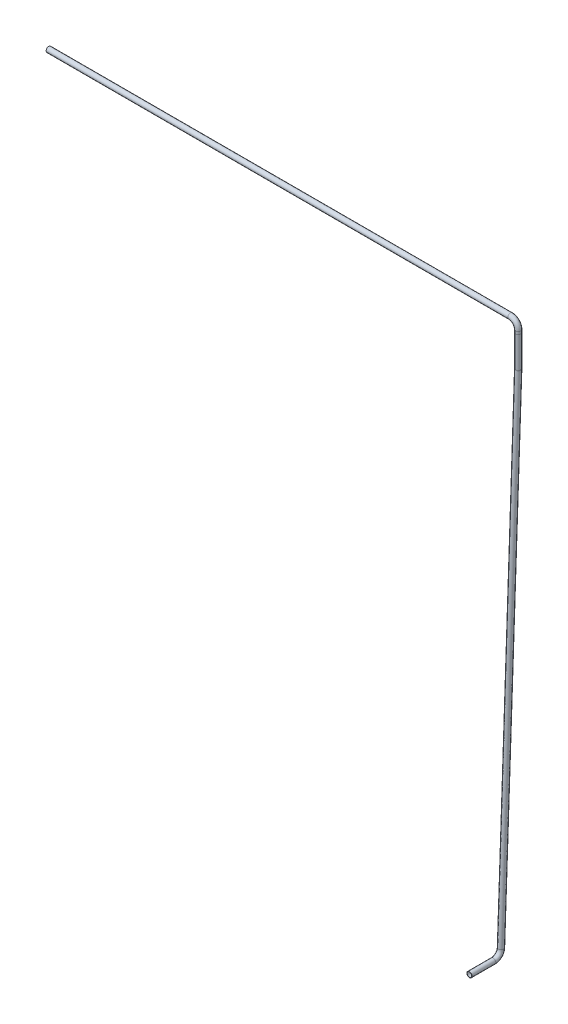
SolidWorks part; units mm, degrees
ref_plane "Front" through (0, 0, 0) normal (0, 0, 1) x (1, 0, 0)
ref_plane "Top" through (0, 0, 0) normal (0, 1, 0) x (1, 0, 0)
ref_plane "Right" through (0, 0, 0) normal (1, 0, 0) x (0, 0, -1)
sketch "Sketch1" plane through (0, 0, 0) normal (0, 0, 1) x (1, 0, 0)
  circle A0 centre (0, 0) radius 12.7
  circle A1 centre (0, 0) radius 11.1125
  dimension "D1" = 25.4
  dimension "D2" = 22.225
sketch "Sketch2" plane through (0, 0, 0) normal (1, 0, 0) x (0, 0, -1)
  line L0 (0, 0) -> (115.6073, 0)
  line L1 (0, 12.7) -> (0, -12.7) construction
  line L2 (50, 0) -> (-50, 0) construction
  line L3 (153.684, 36.7703) -> (237.468, 2436.0284)
  line L4 (237.4989, 2437.8013) -> (237.4989, 2589.3146)
  arc A0 (153.684, 36.7703) -> (115.6073, 0) centre (115.6073, 38.1) cw
  arc A1 (237.4989, 2437.8013) -> (237.468, 2436.0284) centre (186.6989, 2437.8013) cw
  point P9 (152.4, 0)
  point P13 (237.4989, 2436.9146)
  dimension "D4" = 38.1
  dimension "D6" = 50.8
  dimension "D1" = 152.4
  dimension "D2" = 2438.4
  dimension "D3" = 92
  dimension "D5" = 152.4
ref_plane "Plane1" through (0, 0, -237.4989) normal (0, 0, -1) x (0, 1, 0)
sketch "Sketch3" plane through (0, 0, -237.4989) normal (0, 0, -1) x (0, 1, 0)
  line L0 (2589.3146, 0) -> (2602.0146, 0)
  line L1 (2640.1146, -38.1) -> (2640.1146, -2286)
  arc A0 (2640.1146, -38.1) -> (2602.0146, 0) centre (2602.0146, -38.1) ccw
  point P7 (2640.1146, 0)
  dimension "D3" = 38.1
  dimension "D1" = 2286
  dimension "D2" = 50.8
curve "CompCurve1"
sweep "Sweep1" add profiles "Sketch1" path "CompCurve1"
